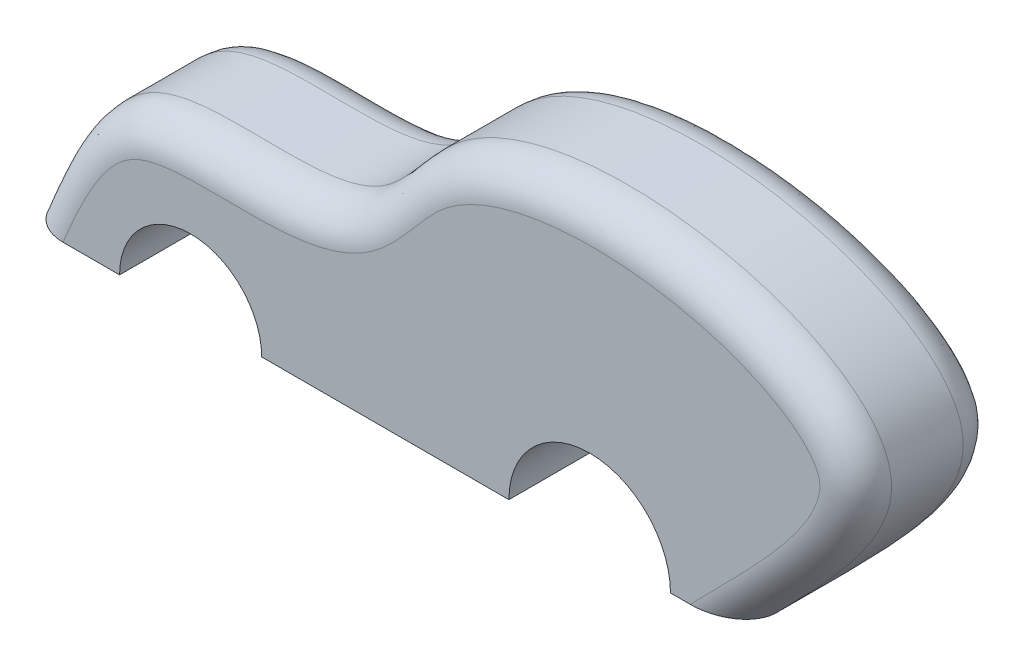
SolidWorks part; units mm, degrees
ref_plane "Front Plane" through (0, 0, 0) normal (0, 0, 1) x (1, 0, 0)
ref_plane "Top Plane" through (0, 0, 0) normal (0, 1, 0) x (1, 0, 0)
ref_plane "Right Plane" through (0, 0, 0) normal (1, 0, 0) x (0, 0, -1)
sketch "Sketch1" plane through (0, 0, 0) normal (0, 0, 1) x (1, 0, 0)
  line L0 (-12.4667, -5.1731) -> (-9.0847, -5.1731)
  line L1 (12.9333, -5.1731) -> (10.4485, -5.1731)
  line L2 (-4.0461, -5.1731) -> (4.7197, -5.1731)
  arc A0 (-9.0847, -5.1731) -> (-4.0461, -5.1731) centre (-6.5654, -5.1731) cw
  arc A1 (4.7197, -5.1731) -> (10.4485, -5.1731) centre (7.5841, -5.1731) cw
  spline S0 degree 3 poles (-12.4667, -5.1731) (-11.6026, -3.0888) (-9.5654, 1.825) (-1.4575, -0.9748) (3.3136, 7.6625) (21.6945, 3.7349) (15.0605, -3.0102) (12.9333, -5.1731) knots 0 0 0 0 0.147101 0.346793 0.437562 0.819645 1 1 1 1
  dimension "D1" = 25.4
extrude "Boss-Extrude1" add sketch "Sketch1" along normal blind 5.08 contours A1 L1 S0 L0 A0 L2
fillet "Fillet5" radius 1.27 1 edges
fillet "Fillet6" radius 1.27 1 edges
